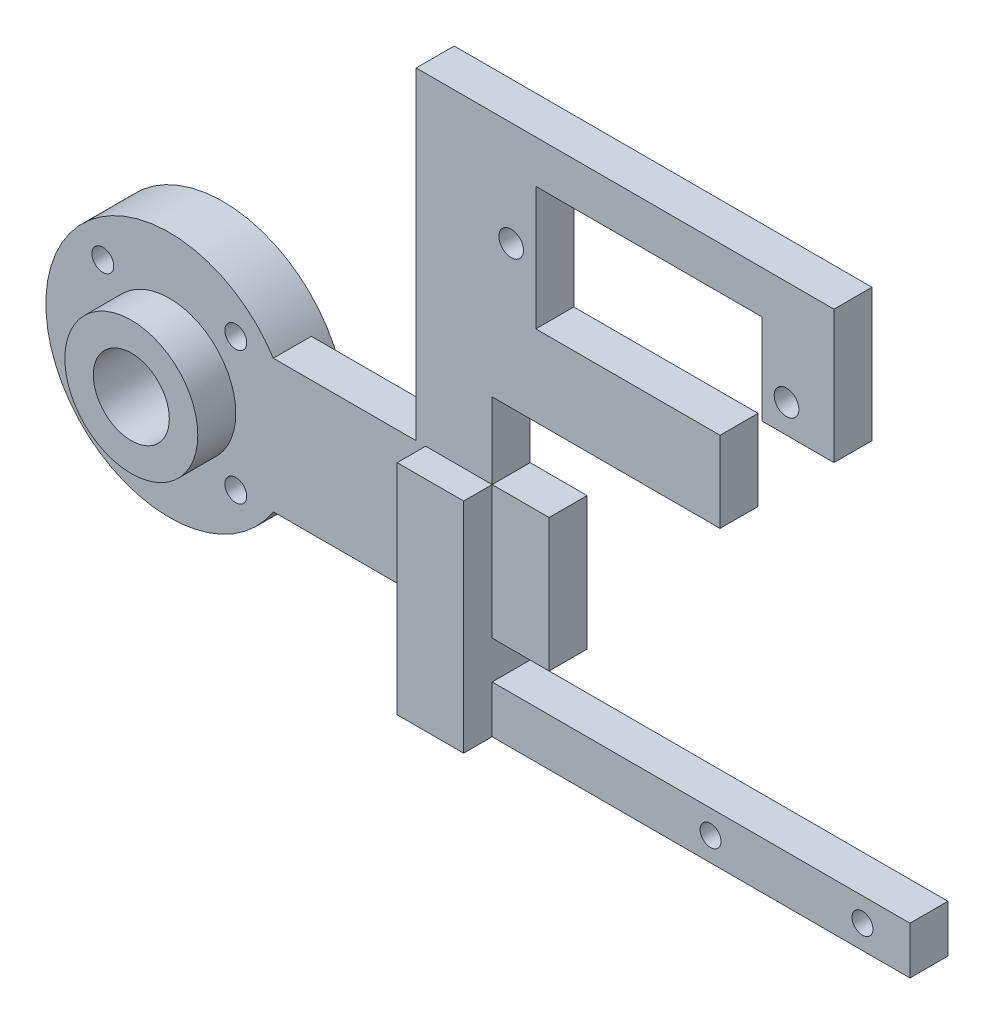
SolidWorks part; units mm, degrees
ref_plane "Front Plane" through (0, 0, 0) normal (0, 0, 1) x (1, 0, 0)
ref_plane "Top Plane" through (0, 0, 0) normal (0, 1, 0) x (1, 0, 0)
ref_plane "Right Plane" through (0, 0, 0) normal (1, 0, 0) x (0, 0, -1)
sketch "Elbow_horn_flange_profile" plane through (0, 0, 0) normal (0, 0, 1) x (1, 0, 0)
  circle A0 centre (0, 0) radius 13
  dimension "D1" = 26
extrude "Elbow_horn_flange" add sketch "Elbow_horn_flange_profile" along normal blind 4
sketch "Forearm_web_profile" plane through (0, 0, 0) normal (0, 0, 1) x (1, 0, 0)
  line L1 (0, -7) -> (40, -7)
  line L2 (0, -7) -> (0, 7)
  line L3 (0, 7) -> (40, 7)
  line L4 (40, -7) -> (40, 7)
  dimension "D1" = 40
  dimension "D2" = 14
  dimension "D3" = 7
extrude "Forearm_web" add sketch "Forearm_web_profile" along normal blind 4
sketch "Gripper_mount_rib_profile" plane through (0, 0, 0) normal (0, 0, 1) x (1, 0, 0)
  line L1 (26, 0) -> (34, 0)
  line L2 (26, 0) -> (26, 30)
  line L3 (26, 30) -> (34, 30)
  line L4 (34, 0) -> (34, 30)
  dimension "D1" = 8
  dimension "D2" = 30
  dimension "D3" = 26
extrude "Gripper_mount_rib" add sketch "Gripper_mount_rib_profile" along normal blind 4
sketch "Gripper_servo_mount_profile" plane through (0, 0, 0) normal (0, 0, 1) x (1, 0, 0)
  line L1 (26, 15) -> (70, 15)
  line L2 (26, 15) -> (26, 41)
  line L3 (26, 41) -> (70, 41)
  line L4 (70, 15) -> (70, 41)
  dimension "D1" = 44
  dimension "D2" = 26
  dimension "D3" = 26
  dimension "D4" = 15
extrude "Gripper_servo_mount" add sketch "Gripper_servo_mount_profile" along normal blind 4
sketch "Grip_SG90_body_clearance_profile" plane through (0, 0, 0) normal (0, 0, 1) x (1, 0, 0)
  line L1 (38.6, 23.5) -> (62.4, 23.5)
  line L2 (38.6, 23.5) -> (38.6, 36.5)
  line L3 (38.6, 36.5) -> (62.4, 36.5)
  line L4 (62.4, 23.5) -> (62.4, 36.5)
  dimension "D1" = 23.8
  dimension "D2" = 13
  dimension "D3" = 38.6
  dimension "D4" = 23.5
extrude "Grip_SG90_body_clearance" cut sketch "Grip_SG90_body_clearance_profile" along normal through all from offset 5
sketch "Moving_finger_sweep_relief_profile" plane through (0, 0, 0) normal (0, 0, 1) x (1, 0, 0)
  line L1 (58, 14) -> (71, 14)
  line L2 (58, 14) -> (58, 27)
  line L3 (58, 27) -> (71, 27)
  line L4 (71, 14) -> (71, 27)
  dimension "D1" = 13
  dimension "D2" = 13
  dimension "D3" = 58
  dimension "D4" = 14
extrude "Moving_finger_sweep_relief" cut sketch "Moving_finger_sweep_relief_profile" along normal through all from offset 5
sketch "Grip_servo_tab_fasteners_profile" plane through (0, 0, 0) normal (0, 0, 1) x (1, 0, 0)
  circle A0 centre (36, 30) radius 1.3
  circle A1 centre (65, 30) radius 1.3
  dimension "D1" = 2.6
  dimension "D2" = 2.6
  dimension "D3" = 36
  dimension "D4" = 65
  dimension "D5" = 30
extrude "Grip_servo_tab_fasteners" cut sketch "Grip_servo_tab_fasteners_profile" along normal through all from offset 50
sketch "Fixed_finger_spine_profile" plane through (0, 0, 0) normal (0, 0, 1) x (1, 0, 0)
  line L1 (30, -16) -> (78, -16)
  line L2 (30, -16) -> (30, -11)
  line L3 (30, -11) -> (78, -11)
  line L4 (78, -16) -> (78, -11)
  dimension "D1" = 48
  dimension "D2" = 5
  dimension "D3" = 30
  dimension "D4" = 11
extrude "Fixed_finger_spine" add sketch "Fixed_finger_spine_profile" along normal blind 4
sketch "Fixed_finger_root_profile" plane through (0, 0, 0) normal (0, 0, 1) x (1, 0, 0)
  line L1 (27, -16) -> (34, -16)
  line L2 (27, -16) -> (27, 7)
  line L3 (27, 7) -> (34, 7)
  line L4 (34, -16) -> (34, 7)
  dimension "D1" = 7
  dimension "D2" = 23
  dimension "D3" = 27
  dimension "D4" = 7
extrude "Fixed_finger_root" add sketch "Fixed_finger_root_profile" along normal blind 7
sketch "Elbow_center_screw_access_profile" plane through (0, 0, 0) normal (0, 0, 1) x (1, 0, 0)
  circle A0 centre (0, 0) radius 4
  dimension "D1" = 8
extrude "Elbow_center_screw_access" cut sketch "Elbow_center_screw_access_profile" along normal through all from offset 50
sketch "Elbow_dowel_support_hub_profile" plane through (0, 0, 0) normal (0, 0, 1) x (1, 0, 0)
  circle A0 centre (0, 0) radius 7
  circle A1 centre (0, 0) radius 4
  dimension "D1" = 14
  dimension "D2" = 8
extrude "Elbow_dowel_support_hub" add sketch "Elbow_dowel_support_hub_profile" along normal blind 4 from offset 4
sketch "Captured_horn_key_boss_profile" plane through (0, 0, 0) normal (0, 0, 1) x (1, 0, 0)
  circle A0 centre (0, 0) radius 13
  dimension "D1" = 26
extrude "Captured_horn_key_boss" add sketch "Captured_horn_key_boss_profile" along normal blind 1.65 from offset 1.65
sketch "Stock_horn_pocket_Hub" plane through (0, 0, 0) normal (0, 0, 1) x (1, 0, 0)
  circle A0 centre (0, 0) radius 3.55
  dimension "D1" = 7.1
extrude "Key_pocket_Hub" cut sketch "Stock_horn_pocket_Hub" along normal blind 1.65 from offset 1.65
sketch "Stock_horn_pocket_Horizontal" plane through (0, 0, 0) normal (0, 0, 1) x (1, 0, 0)
  line L1 (-8.15, -2.1) -> (8.15, -2.1)
  line L2 (-8.15, -2.1) -> (-8.15, 2.1)
  line L3 (-8.15, 2.1) -> (8.15, 2.1)
  line L4 (8.15, -2.1) -> (8.15, 2.1)
  dimension "D1" = 16.3
  dimension "D2" = 4.2
  dimension "D3" = 8.15
  dimension "D4" = 2.1
extrude "Key_pocket_Horizontal" cut sketch "Stock_horn_pocket_Horizontal" along normal blind 1.65 from offset 1.65
sketch "Stock_horn_pocket_Vertical" plane through (0, 0, 0) normal (0, 0, 1) x (1, 0, 0)
  line L1 (-2.1, -8.15) -> (2.1, -8.15)
  line L2 (-2.1, -8.15) -> (-2.1, 8.15)
  line L3 (-2.1, 8.15) -> (2.1, 8.15)
  line L4 (2.1, -8.15) -> (2.1, 8.15)
  dimension "D1" = 4.2
  dimension "D2" = 16.3
  dimension "D3" = 2.1
  dimension "D4" = 8.15
extrude "Key_pocket_Vertical" cut sketch "Stock_horn_pocket_Vertical" along normal blind 1.65 from offset 1.65
sketch "Stock_horn_pocket_Rounded_tips" plane through (0, 0, 0) normal (0, 0, 1) x (1, 0, 0)
  circle A0 centre (8.15, 0) radius 2.1
  circle A1 centre (-8.15, 0) radius 2.1
  circle A2 centre (0, 8.15) radius 2.1
  circle A3 centre (0, -8.15) radius 2.1
  dimension "D1" = 4.2
  dimension "D2" = 4.2
  dimension "D3" = 4.2
  dimension "D4" = 4.2
  dimension "D5" = 8.15
  dimension "D6" = 8.15
  dimension "D7" = 8.15
  dimension "D8" = 8.15
extrude "Key_pocket_Rounded_tips" cut sketch "Stock_horn_pocket_Rounded_tips" along normal blind 1.65 from offset 1.65
sketch "Unmodified_horn_capture_M2_profile" plane through (0, 0, 0) normal (0, 0, 1) x (1, 0, 0)
  circle A0 centre (7, 7) radius 1.15
  circle A1 centre (-7, 7) radius 1.15
  circle A2 centre (-7, -7) radius 1.15
  circle A3 centre (7, -7) radius 1.15
  dimension "D1" = 2.3
  dimension "D2" = 2.3
  dimension "D3" = 2.3
  dimension "D4" = 2.3
  dimension "D5" = 7
  dimension "D6" = 7
  dimension "D7" = 7
  dimension "D8" = 7
extrude "Unmodified_horn_capture_M2" cut sketch "Unmodified_horn_capture_M2_profile" along normal through all from offset 50
sketch "Horn_center_hub_clearance" plane through (0, 0, 0) normal (0, 0, 1) x (1, 0, 0)
  circle A0 centre (0, 0) radius 4
  dimension "D1" = 8
extrude "Hub_clearance_in_key_boss_only" cut sketch "Horn_center_hub_clearance" along normal blind 1.65 from offset 1.65
sketch "Fixed_pad_keeper_fasteners_profile" plane through (0, 0, 0) normal (0, 0, 1) x (1, 0, 0)
  circle A0 centre (57, -13.5) radius 1.1
  circle A1 centre (73, -13.5) radius 1.1
  dimension "D1" = 2.2
  dimension "D2" = 2.2
  dimension "D3" = 57
  dimension "D4" = 73
  dimension "D5" = 13.5
extrude "Fixed_pad_keeper_fasteners" cut sketch "Fixed_pad_keeper_fasteners_profile" along normal through all from offset 50
